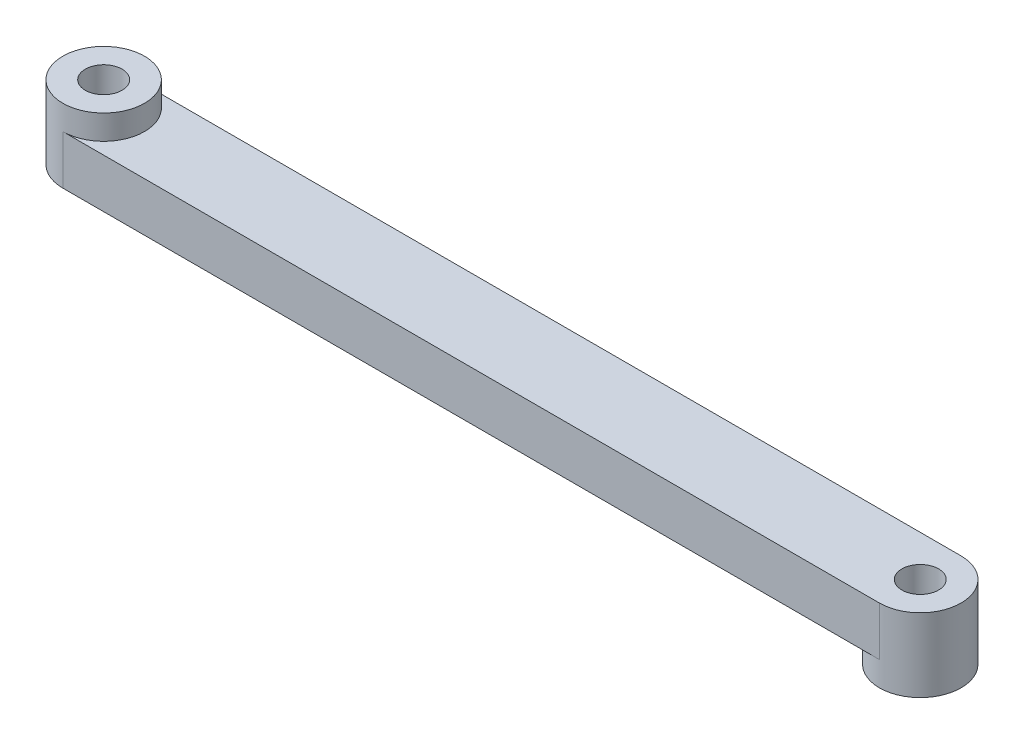
SolidWorks part; units mm, degrees
ref_plane "Front Plane" through (0, 0, 0) normal (0, 0, 1) x (1, 0, 0)
ref_plane "Top Plane" through (0, 0, 0) normal (0, 1, 0) x (1, 0, 0)
ref_plane "Right Plane" through (0, 0, 0) normal (1, 0, 0) x (0, 0, -1)
sketch "Sketch1" plane through (0, 0, 0) normal (0, 1, 0) x (1, 0, 0)
  line L0 (0, 0) -> (0, 9950.1565) construction
  line L1 (0, 0) -> (9950.1565, 0) construction
  line L2 (0, 5) -> (100, 5)
  line L3 (0, -5) -> (100, -5)
  circle A0 centre (0, 0) radius 2.25
  circle A1 centre (100, 0) radius 2.25
  arc A2 (0, 5) -> (0, -5) centre (0, 0) ccw
  arc A3 (100, -5) -> (100, 5) centre (100, 0) ccw
  point P15 (100, 5)
  dimension "D1" = 4.5
  dimension "D3" = 10
  dimension "D2" = 100
extrude "Boss-Extrude1" add sketch "Sketch1" along normal blind 12
sketch "Sketch2" plane through (0, 12, 0) normal (0, 1, 0) x (1, 0, 0)
  circle A0 centre (0, 0) radius 5
extrude "Cut-Extrude-Thin1" cut sketch "Sketch2" against normal blind 3 thin
sketch "Sketch3" plane through (0, 0, 0) normal (0, -1, 0) x (1, 0, 0)
  circle A0 centre (100, 0) radius 5
extrude "Cut-Extrude-Thin2" cut sketch "Sketch3" against normal blind 3 thin
